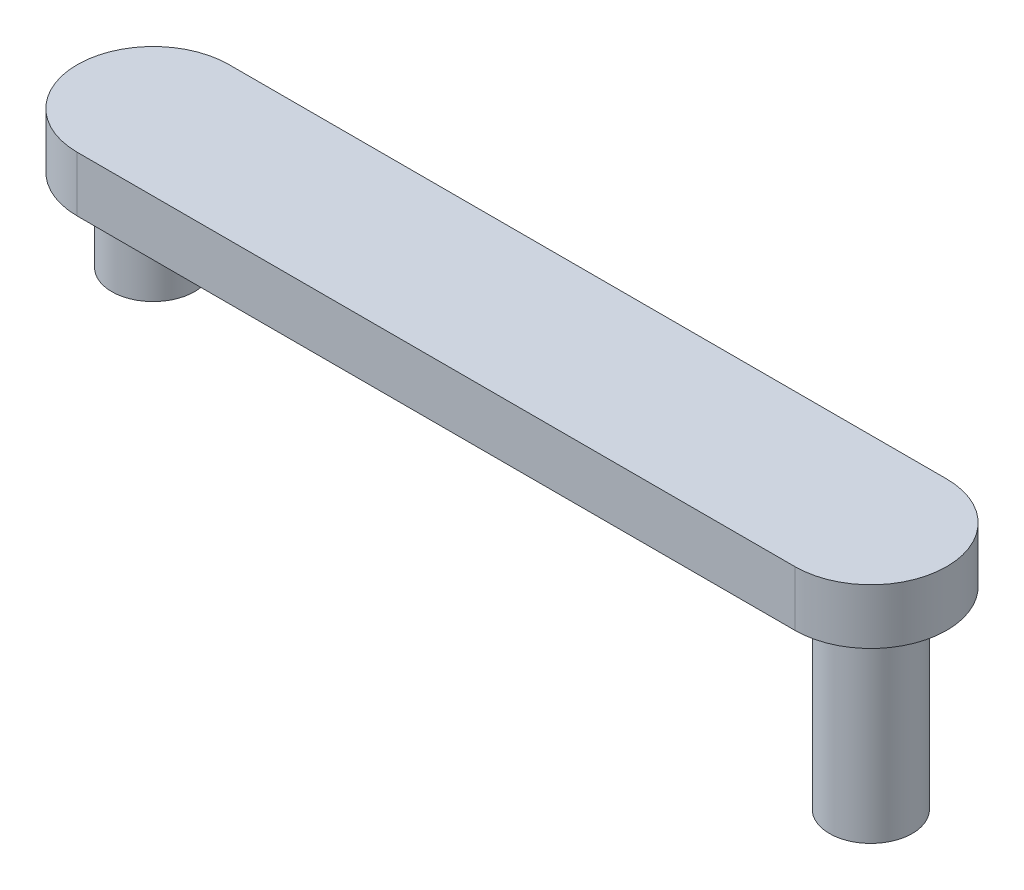
SolidWorks part; units mm, degrees
ref_plane "Front Plane" through (0, 0, 0) normal (0, 0, 1) x (1, 0, 0)
ref_plane "Top Plane" through (0, 0, 0) normal (0, 1, 0) x (1, 0, 0)
ref_plane "Right Plane" through (0, 0, 0) normal (1, 0, 0) x (0, 0, -1)
sketch "Sketch1" plane through (0, 0, 0) normal (0, 1, 0) x (1, 0, 0)
  line L0 (-11.8981, 0) -> (13.5671, 0) construction
  circle A0 centre (0, 0) radius 1.5
  dimension "D1" = 3
extrude "Boss-Extrude1" add sketch "Sketch1" along normal blind 3
sketch "Sketch2" plane through (0, 3, 0) normal (0, 1, 0) x (1, 0, 0)
  line L0 (-6.8584, 0) -> (34.6919, 0) construction
  line L1 (0, 2.75) -> (26, 2.75)
  line L2 (0, -2.75) -> (26, -2.75)
  arc A0 (0, 2.75) -> (0, -2.75) centre (0, 0) ccw
  arc A1 (26, -2.75) -> (26, 2.75) centre (26, 0) ccw
  dimension "D1" = 5.5
  dimension "D2" = 5.5
  dimension "D3" = 26
extrude "Boss-Extrude2" add sketch "Sketch2" along normal blind 2
sketch "Sketch3" plane through (0, 3, 0) normal (0, -1, 0) x (1, 0, 0)
  arc A0 (26, -2.75) -> (26, 2.75) centre (26, 0) ccw construction
  arc A1 (26, -2.75) -> (26, 2.75) centre (26, 0) ccw
  circle A2 centre (26, 0) radius 1.5
  dimension "D1" = 3
extrude "Boss-Extrude3" add sketch "Sketch3" along normal blind 7 contours A2
